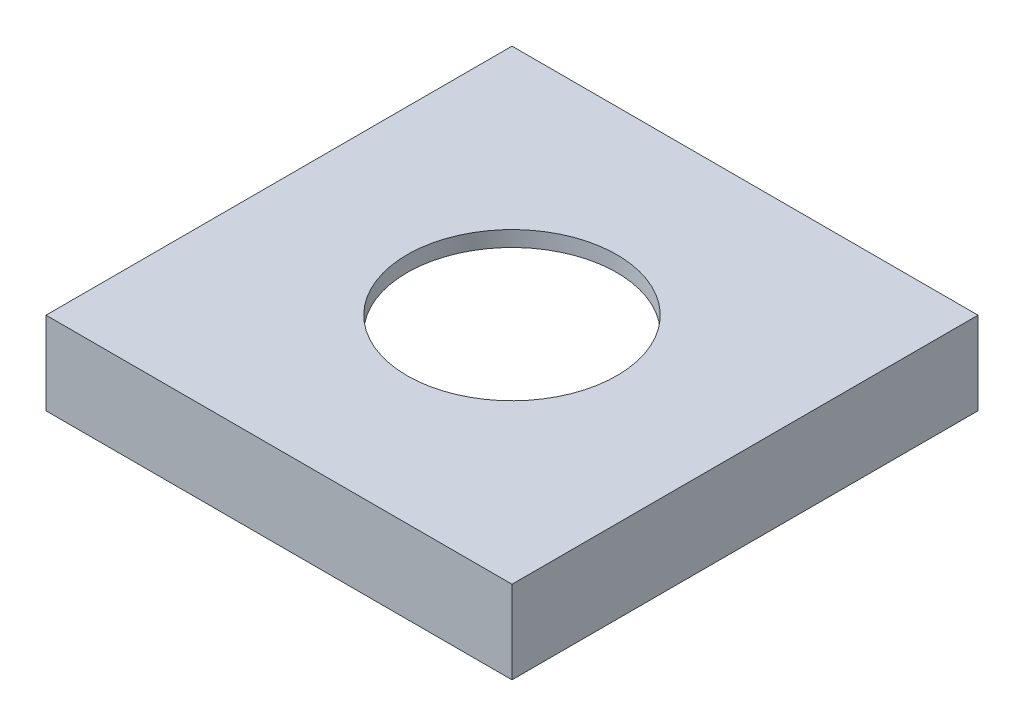
SolidWorks part; units mm, degrees
material "PLA"
ref_plane "Front Plane" through (0, 0, 0) normal (0, 0, 1) x (1, 0, 0)
ref_plane "Top Plane" through (0, 0, 0) normal (0, 1, 0) x (1, 0, 0)
ref_plane "Right Plane" through (0, 0, 0) normal (1, 0, 0) x (0, 0, -1)
sketch "Sketch1" plane through (0, 0, 0) normal (0, 1, 0) x (1, 0, 0)
  line L0 (18, 18) -> (18, -18)
  line L1 (-15.6, 15.6) -> (15.6, 15.6)
  line L2 (-15.6, 15.6) -> (-15.6, -15.6)
  line L3 (-15.6, -15.6) -> (15.6, -15.6)
  line L4 (15.6, 15.6) -> (15.6, -15.6)
  line L5 (-15.6, 15.6) -> (15.6, -15.6) construction
  line L6 (-15.6, -15.6) -> (15.6, 15.6) construction
  line L7 (-18, -18) -> (18, -18)
  line L8 (-18, 18) -> (-18, -18)
  line L9 (-18, 18) -> (18, 18)
  point P0 (0, 0)
  dimension "D1" = 31.2
  dimension "D2" = 2.4
extrude "Boss-Extrude1" add sketch "Sketch1" along normal blind 5.2
sketch "Sketch2" plane through (0, 5.2, 0) normal (0, 1, 0) x (1, 0, 0)
  line L4 (18, 18) -> (-18, 18)
  line L5 (-18, 18) -> (-18, -18)
  line L6 (-18, -18) -> (18, -18)
  line L7 (18, -18) -> (18, 18)
  line L8 (18, 18) -> (-18, 18)
  line L9 (-18, 18) -> (-18, -18)
  line L10 (-18, -18) -> (18, -18)
  line L11 (18, -18) -> (18, 18)
  line L22 (-10.8, -10.8) -> (10.8, -10.8)
  line L23 (10.8, -10.8) -> (10.8, 10.8)
  line L24 (10.8, 10.8) -> (-10.8, 10.8)
  line L25 (-10.8, 10.8) -> (-10.8, -10.8)
  line L26 (-10.8, -10.8) -> (10.8, -10.8)
  line L27 (10.8, -10.8) -> (10.8, 10.8)
  line L28 (10.8, 10.8) -> (-10.8, 10.8)
  line L29 (-10.8, 10.8) -> (-10.8, -10.8)
  dimension "D1" = 0
  dimension "D2" = 4.8
extrude "Boss-Extrude2" add sketch "Sketch2" along normal blind 1.2
sketch "Sketch3" plane through (0, 6.4, 0) normal (0, 1, 0) x (1, 0, 0)
  line L0 (-10.8, -10.8) -> (10.8, -10.8) construction
  line L1 (10.8, -10.8) -> (10.8, 10.8) construction
  line L2 (10.8, 10.8) -> (-10.8, 10.8) construction
  line L3 (-10.8, 10.8) -> (-10.8, -10.8) construction
  line L4 (-10.8, -10.8) -> (10.8, -10.8)
  line L5 (10.8, -10.8) -> (10.8, 10.8)
  line L6 (10.8, 10.8) -> (-10.8, 10.8)
  line L7 (-10.8, 10.8) -> (-10.8, -10.8)
  circle A0 centre (0, 0) radius 8.1
  dimension "D1" = 16.2
extrude "Boss-Extrude3" add sketch "Sketch3" against normal up to surface (1.2 mm away) up to face at (0, 5.2, 0)
equation "\"D1@Sketch1\"=30.8+.4"
